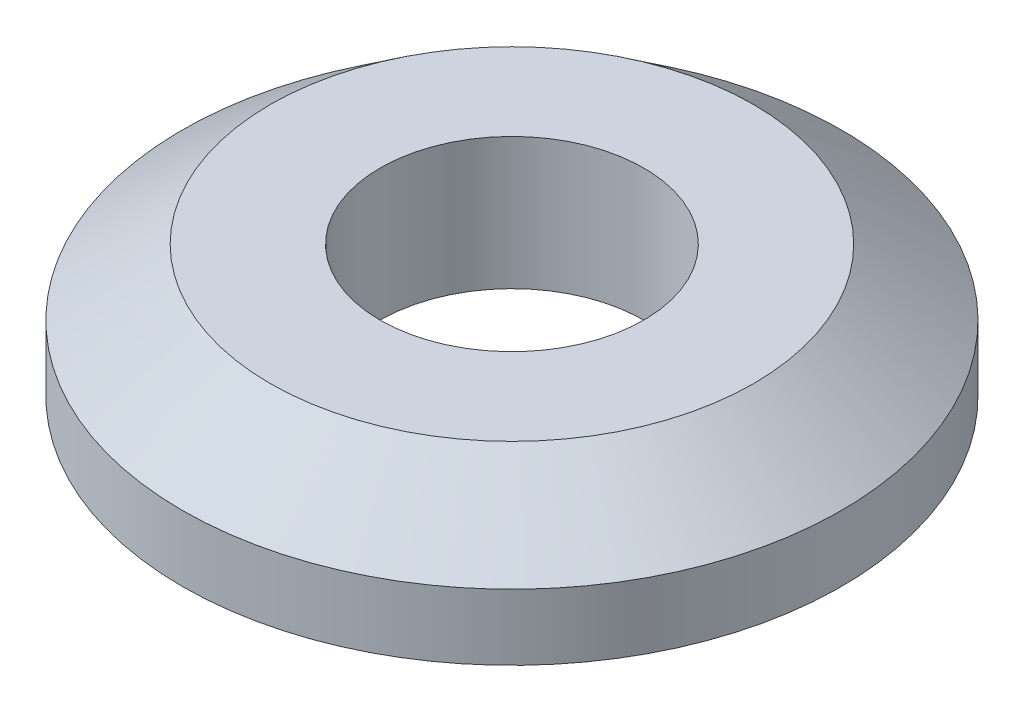
SolidWorks part; units mm, degrees
ref_plane "前视基准面" through (0, 0, 0) normal (0, 0, 1) x (1, 0, 0)
ref_plane "上视基准面" through (0, 0, 0) normal (0, 1, 0) x (1, 0, 0)
ref_plane "右视基准面" through (0, 0, 0) normal (1, 0, 0) x (0, 0, -1)
sketch "草图1" plane through (0, 0, 0) normal (0, 1, 0) x (1, 0, 0)
  circle A0 centre (0, 0) radius 7.5
  circle A1 centre (0, 0) radius 3
  dimension "D1" = 15
  dimension "D2" = 6
extrude "凸台-拉伸1" add sketch "草图1" along normal blind 3
chamfer "倒角1" distance 1.5 distance2 2 1 edges at (0, 3, 7.5)
